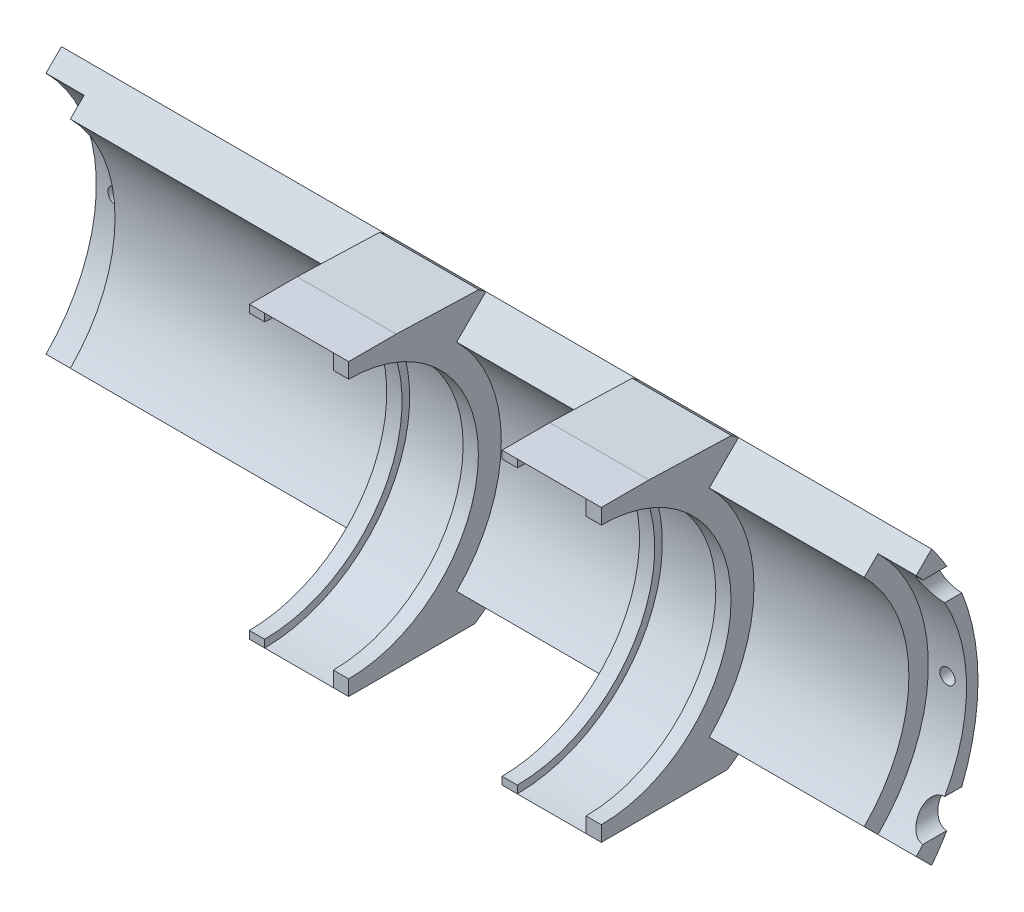
SolidWorks part; units mm, degrees
ref_plane "Plan de face" through (0, 0, 0) normal (0, 0, 1) x (1, 0, 0)
ref_plane "Plan de dessus" through (0, 0, 0) normal (0, 1, 0) x (1, 0, 0)
ref_plane "Plan de droite" through (0, 0, 0) normal (1, 0, 0) x (0, 0, -1)
sketch "Esquisse1" plane through (0, 0, 0) normal (1, 0, 0) x (0, 0, -1)
  line L0 (17.9753, 17.9475) -> (17.9753, -17.9475) construction
  line L1 (14.1443, 14.14) -> (14.1443, -14.14) construction
  line L2 (0, 3.9479) -> (0, -6.61) construction
  line L3 (14.1443, 14.14) -> (17.9753, 17.9475)
  line L4 (14.1443, -14.14) -> (17.9753, -17.9475)
  circle A0 centre (0, 0) radius 20 construction
  circle A1 centre (-5.5, 0) radius 29.55 construction
  arc A2 (14.1443, 14.14) -> (14.1443, -14.14) centre (0, 0) cw
  arc A3 (17.9753, 17.9475) -> (17.9753, -17.9475) centre (-5.5, 0) cw
  dimension "D1" = 40
  dimension "D2" = 59.1
  dimension "D5" = 35.8949
  dimension "D3" = 0
  dimension "D4" = 5.5
  dimension "D6" = 28.28
extrude "Boss.-Extru.1" add sketch "Esquisse1" along normal blind 114
sketch "Esquisse2" plane through (0, 0, 0) normal (-1, 0, 0) x (0, 0, 1)
  circle A0 centre (0, 0) radius 22.55
  dimension "D1" = 45.1
extrude "Enlèv. mat.-Extru.2" cut sketch "Esquisse2" against normal blind 5
sketch "Esquisse4" plane through (114, 0, 0) normal (1, 0, 0) x (0, 0, -1)
  circle A0 centre (0, 0) radius 22.55
  dimension "D1" = 45.1
extrude "Enlèv. mat.-Extru.3" cut sketch "Esquisse4" against normal blind 5
sketch "Esquisse5" plane through (0, 0, 0) normal (0, 0, 1) x (1, 0, 0)
  line L0 (0, 15.9376) -> (0, -15.9376) construction
  line L1 (114, -15.9376) -> (114, 15.9376) construction
  circle A0 centre (2.5, 0) radius 1
  circle A1 centre (111.5, 0) radius 1
  dimension "D1" = 2
  dimension "D2" = 2
  dimension "D3" = 0
  dimension "D4" = 0
  dimension "D5" = 2.5
  dimension "D6" = 2.5
extrude "Enlèv. mat.-Extru.4" cut sketch "Esquisse5" against normal through all
ref_plane "Plan1" through (88.7, 0, 0) normal (1, 0, 0) x (0, 0, -1)
sketch "Esquisse6" plane through (88.7, 0, 0) normal (1, 0, 0) x (0, 0, -1)
  line L0 (0, 17) -> (0, 20)
  line L1 (0, -17) -> (0, -20)
  arc A0 (0, -17) -> (0, 17) centre (0, 0) ccw
  arc A1 (0, -20) -> (0, 20) centre (0, 0) ccw
  dimension "D1" = 34
extrude "Boss.-Extru.2" add sketch "Esquisse6" against normal blind 2
sketch "Esquisse7" plane through (86.7, 0, 0) normal (-1, 0, 0) x (0, 0, 1)
  line L0 (0, 20) -> (0, 19)
  line L1 (0, -20) -> (0, -19)
  arc A0 (0, 19) -> (0, -19) centre (0, 0) ccw
  arc A1 (0, 20) -> (0, -20) centre (0, 0) ccw
  dimension "D1" = 38
extrude "Boss.-Extru.3" add sketch "Esquisse7" along normal blind 9
sketch "Esquisse8" plane through (77.7, 0, 0) normal (-1, 0, 0) x (0, 0, 1)
  line L0 (0, 20) -> (0, 18)
  line L1 (0, -20) -> (0, -18)
  arc A0 (0, 18) -> (0, -18) centre (0, 0) ccw
  arc A1 (0, 20) -> (0, -20) centre (0, 0) ccw
  dimension "D1" = 36
extrude "Boss.-Extru.4" add sketch "Esquisse8" along normal blind 2
ref_plane "Plan2" through (55.6, 0, 0) normal (1, 0, 0) x (0, 0, -1)
sketch "Esquisse9" plane through (55.6, 0, 0) normal (1, 0, 0) x (0, 0, -1)
  line L0 (0, 20) -> (0, 17)
  line L1 (0, -20) -> (0, -17)
  arc A0 (0, -17) -> (0, 17) centre (0, 0) ccw
  arc A1 (0, 20) -> (0, -20) centre (0, 0) cw
extrude "Boss.-Extru.5" add sketch "Esquisse9" against normal blind 2
sketch "Esquisse10" plane through (53.6, 0, 0) normal (-1, 0, 0) x (0, 0, 1)
  line L0 (0, 20) -> (0, 19)
  line L1 (0, -20) -> (0, -19)
  arc A0 (0, 19) -> (0, -19) centre (0, 0) ccw
  arc A1 (0, 20) -> (0, -20) centre (0, 0) ccw
  dimension "D1" = 38
extrude "Boss.-Extru.6" add sketch "Esquisse10" along normal blind 9
sketch "Esquisse11" plane through (44.6, 0, 0) normal (-1, 0, 0) x (0, 0, 1)
  line L0 (0, 20) -> (0, 18)
  line L1 (0, -20) -> (0, -18)
  arc A0 (0, 18) -> (0, -18) centre (0, 0) ccw
  arc A1 (0, 20) -> (0, -20) centre (0, 0) ccw
extrude "Boss.-Extru.7" add sketch "Esquisse11" along normal blind 2
sketch "Esquisse12" plane through (88.7, 0, 0) normal (1, 0, 0) x (0, 0, -1)
  line L1 (0, -20) -> (13.7518, -20)
  line L2 (0, -20) -> (0, -19)
  line L3 (0, -19) -> (13.7518, -19)
  line L4 (13.7518, -20) -> (13.7518, -19)
  line L5 (0, 20) -> (11.1675, 20)
  line L6 (0, 20) -> (0, 19)
  line L7 (0, 19) -> (11.1675, 19)
  line L8 (11.1675, 20) -> (11.1675, 19)
  dimension "D1" = 2
  dimension "D2" = 2
extrude "Enlèv. mat.-Extru.5" cut sketch "Esquisse12" against normal through all
sketch "Esquisse13" plane through (88.7, 0, 0) normal (1, 0, 0) x (0, 0, -1)
  line L1 (17.9753, 17.9475) -> (14.1443, 14.14)
  line L2 (14.1443, -14.14) -> (17.9753, -17.9475)
  line L4 (6.245, 19) -> (17.4397, 18.6272)
  line L5 (6.245, -19) -> (17.1319, -19)
  arc A0 (14.1443, 14.14) -> (6.245, 19) centre (0, 0) ccw
  arc A1 (6.245, -19) -> (14.1443, -14.14) centre (0, 0) ccw
  arc A2 (17.9753, 17.9475) -> (17.4397, 18.6272) centre (-5.5, 0) ccw
  arc A3 (17.9753, -17.9475) -> (17.1319, -19) centre (-5.5, 0) cw
extrude "Boss.-Extru.8" add sketch "Esquisse13" against normal up to surface (13 mm away) up to face at (75.7, 0, -8.1507)
sketch "Esquisse14" plane through (55.6, 0, 0) normal (1, 0, 0) x (0, 0, -1)
  line L0 (14.1443, 14.14) -> (17.9753, 17.9475)
  line L2 (14.1443, -14.14) -> (17.9753, -17.9475)
  line L4 (6.245, 19) -> (17.4397, 18.6272)
  line L5 (6.245, -19) -> (17.1319, -19)
  arc A0 (14.1443, 14.14) -> (6.245, 19) centre (0, 0) ccw
  arc A1 (14.1443, -14.14) -> (6.245, -19) centre (0, 0) cw
  arc A2 (17.4397, 18.6272) -> (17.9753, 17.9475) centre (-5.5, 0) cw
  arc A3 (17.9753, -17.9475) -> (17.1319, -19) centre (-5.5, 0) cw
extrude "Boss.-Extru.9" add sketch "Esquisse14" against normal up to surface (13 mm away) up to face at (42.6, 0, -8.1507)
sketch "Esquisse15" plane through (88.7, 0, 0) normal (1, 0, 0) x (0, 0, -1)
  line L0 (14.4093, 20.2987) -> (16.9015, 24.7608)
  line L1 (16.9015, 24.7608) -> (24.8905, 20.2987)
  line L2 (24.8905, 20.2987) -> (20.896, 15.394)
  line L3 (14.4093, -20.2987) -> (16.9015, -24.7608)
  line L4 (16.9015, -24.7608) -> (22.9342, -18.4643)
  line L5 (22.9342, -18.4643) -> (20.4311, -15.8488)
  arc A1 (14.4093, -20.2987) -> (20.4311, -15.8488) centre (0, 5.5) ccw
  arc A2 (20.896, 15.394) -> (14.4093, 20.2987) centre (0, -5.5) ccw
  dimension "D3" = 59.1
  dimension "D1" = 5.5
  dimension "D2" = 5.5
extrude "Enlèv. mat.-Extru.6" cut sketch "Esquisse15" against normal through all
sketch "Esquisse16" plane through (0, 0, 0) normal (0, 0, 1) x (1, 0, 0)
  line L0 (114, -15.9376) -> (114, 15.9376) construction
  circle A0 centre (114, 13) radius 2
  circle A1 centre (114, -13) radius 2
  circle A2 centre (111.5, 0) radius 1 construction
  dimension "D2" = 4
  dimension "D3" = 4
  dimension "D5" = 13
  dimension "D1" = 0
  dimension "D4" = 0
  dimension "D6" = 13
extrude "Enlèv. mat.-Extru.7" cut sketch "Esquisse16" against normal through all both and the other way through all
